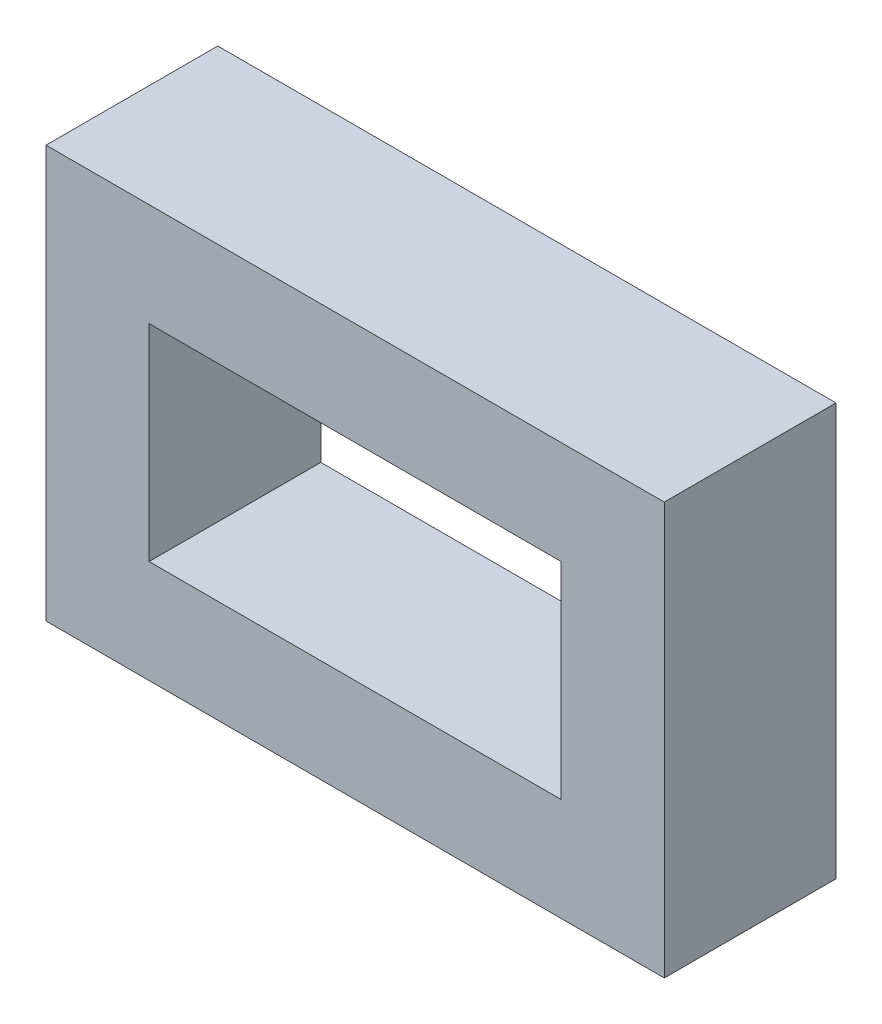
SolidWorks part; units mm, degrees
ref_plane "Front Plane" through (0, 0, 0) normal (0, 0, 1) x (1, 0, 0)
ref_plane "Top Plane" through (0, 0, 0) normal (0, 1, 0) x (1, 0, 0)
ref_plane "Right Plane" through (0, 0, 0) normal (1, 0, 0) x (0, 0, -1)
sketch "Sketch1" plane through (0, 0, 0) normal (0, 0, 1) x (1, 0, 0)
  line L1 (0, 0) -> (18, 0)
  line L2 (0, 0) -> (0, 12)
  line L3 (0, 12) -> (18, 12)
  line L4 (18, 0) -> (18, 12)
  line L6 (3, 3) -> (15, 3)
  line L7 (3, 3) -> (3, 9)
  line L8 (3, 9) -> (15, 9)
  line L9 (15, 3) -> (15, 9)
  dimension "D1" = 3
  dimension "D2" = 15
  dimension "D3" = 18
  dimension "D4" = 3
  dimension "D5" = 9
  dimension "D6" = 12
extrude "Profile" add sketch "Sketch1" along normal blind 5
equation "\"Profile_Depth\"= 5mm"
equation "\"D1@Profile\" = \"Profile_Depth\""
equation "\"Profile_Sketch_1\"= 3mm"
equation "\"D1@Sketch1\" = \"Profile_Sketch_1\""
equation "\"Profile_Sketch_2\"= 15mm"
equation "\"D2@Sketch1\" = \"Profile_Sketch_2\""
equation "\"Profile_Sketch_3\"= 18mm"
equation "\"D3@Sketch1\" = \"Profile_Sketch_3\""
equation "\"Profile_Sketch_4\"= 3mm"
equation "\"D4@Sketch1\" = \"Profile_Sketch_4\""
equation "\"Profile_Sketch_5\"= 9mm"
equation "\"D5@Sketch1\" = \"Profile_Sketch_5\""
equation "\"Profile_Sketch_6\"= 12mm"
equation "\"D6@Sketch1\" = \"Profile_Sketch_6\""
equation "\"EnvelopeWidth\"= 18mm"
equation "\"EnvelopeHeight\"= 12mm"
